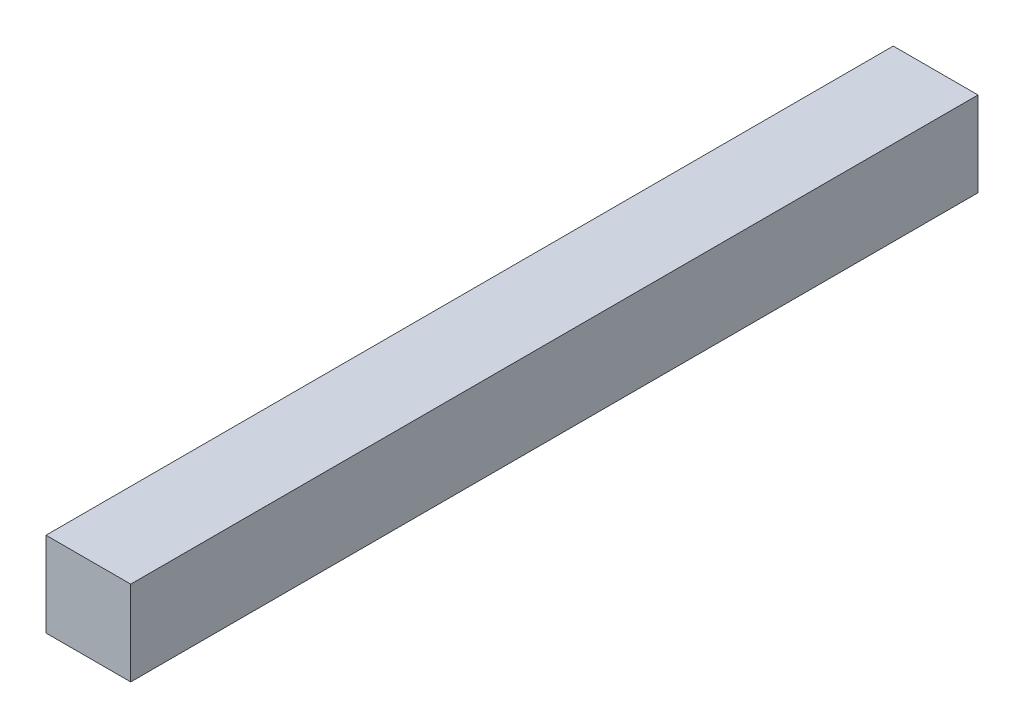
SolidWorks part; units mm, degrees
ref_plane "Front" through (0, 0, 0) normal (0, 0, 1) x (1, 0, 0)
ref_plane "Top" through (0, 0, 0) normal (0, 1, 0) x (1, 0, 0)
ref_plane "Right" through (0, 0, 0) normal (1, 0, 0) x (0, 0, -1)
other "Configuration Table"
sketch "Sketch1" plane through (0, 0, 0) normal (0, 0, 1) x (1, 0, 0)
  line L1 (0, 0) -> (25.4, 0)
  line L2 (0, 0) -> (0, 25.4)
  line L3 (0, 25.4) -> (25.4, 25.4)
  line L4 (25.4, 0) -> (25.4, 25.4)
  dimension "D1" = 25.4
  dimension "D2" = 25.4
extrude "Extrude1" add sketch "Sketch1" against normal blind 254
